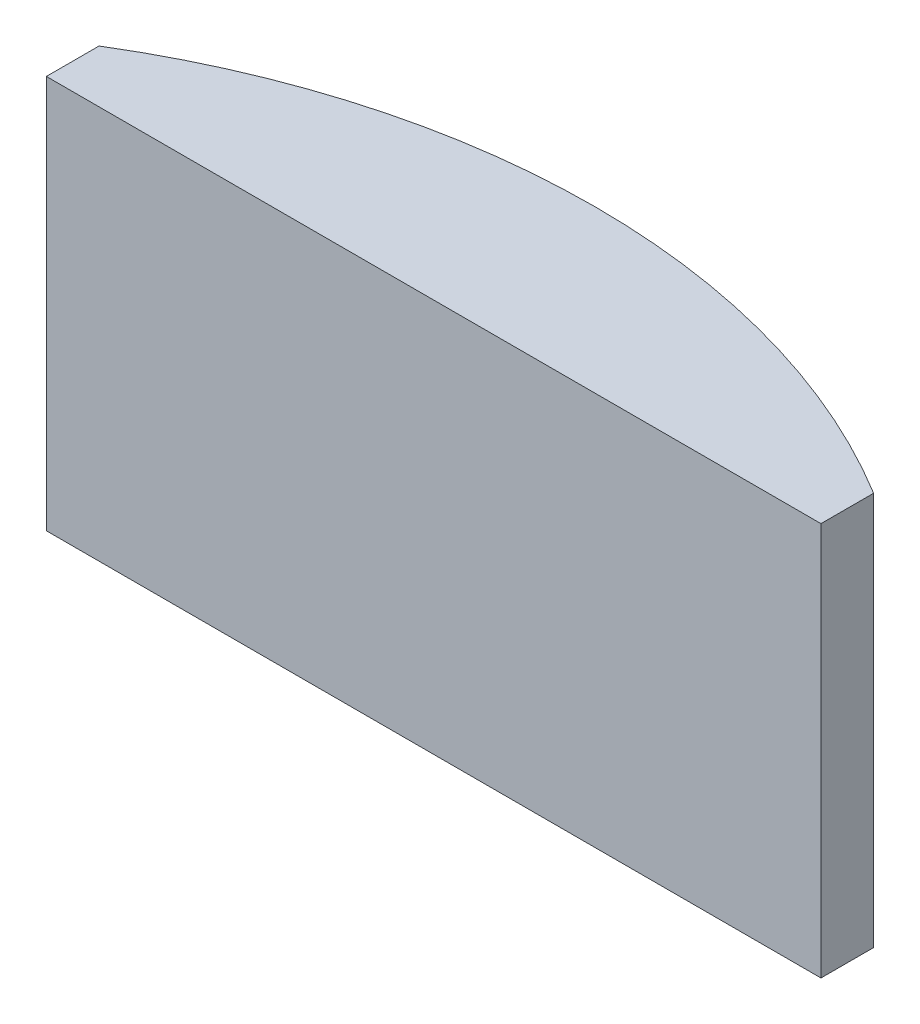
SolidWorks part; units mm, degrees
ref_plane "Front Plane" through (0, 0, 0) normal (0, 0, 1) x (1, 0, 0)
ref_plane "Top Plane" through (0, 0, 0) normal (0, 1, 0) x (1, 0, 0)
ref_plane "Right Plane" through (0, 0, 0) normal (1, 0, 0) x (0, 0, -1)
other "Default"
sketch "Sketch1" plane through (0, 0, 0) normal (0, 1, 0) x (1, 0, 0)
  line L0 (-12.5, 20.4878) -> (12.5, 20.4878)
  circle A0 centre (0, 0) radius 24 construction
  arc A1 (-12.5, 20.4878) -> (12.5, 20.4878) centre (0, 0) cw
  point P6 (0, 24)
  dimension "Diameter" = 48
  dimension "Length" = 25
extrude "Boss-Extrude1" add sketch "Sketch1" along normal mid plane 12.7
sketch "Sketch2" plane through (0, 0, -20.4878) normal (0, 0, 1) x (1, 0, 0)
  line L0 (-12.5, 6.35) -> (12.5, 6.35) construction
  line L1 (-12.5, -6.35) -> (12.5, -6.35)
  line L2 (-12.5, -6.35) -> (-12.5, 6.35)
  line L3 (-12.5, 6.35) -> (12.5, 6.35)
  line L4 (12.5, -6.35) -> (12.5, 6.35)
  line L5 (-12.5, -6.35) -> (12.5, 6.35) construction
  line L6 (-12.5, 6.35) -> (12.5, -6.35) construction
  point P0 (0, 0)
  dimension "TabWidth" = 25
extrude "Boss-Extrude2" add sketch "Sketch2" along normal blind 1.7
